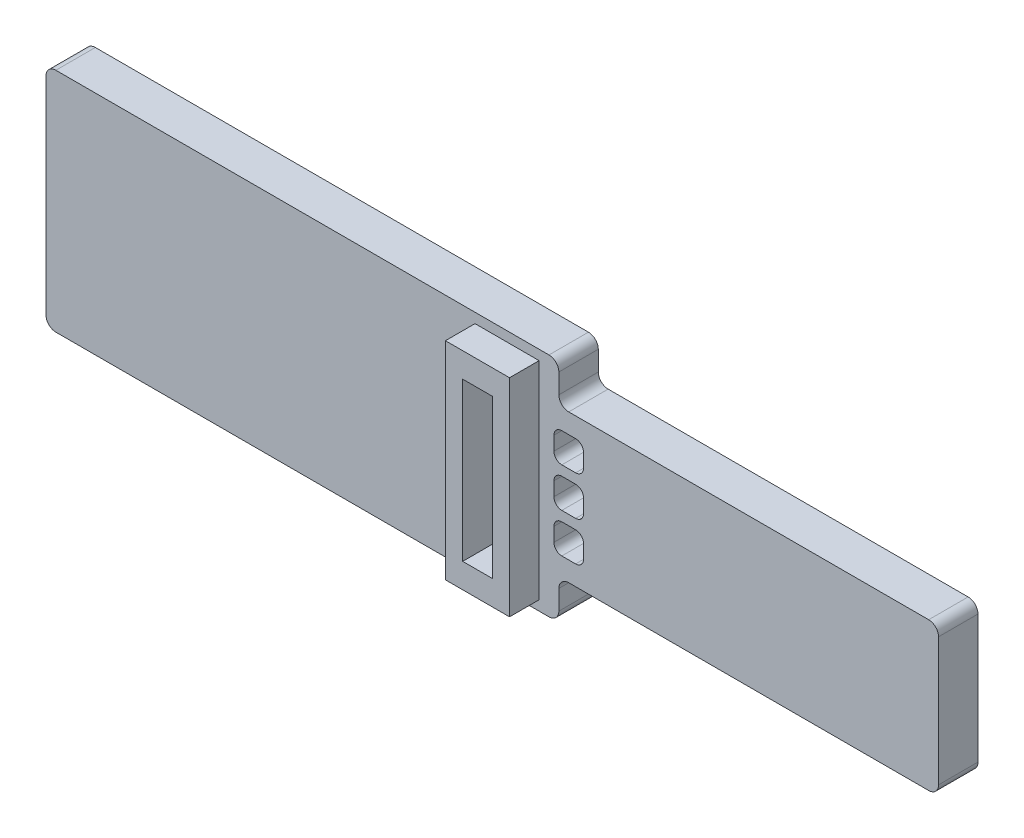
SolidWorks part; units mm, degrees
ref_plane "Front Plane" through (0, 0, 0) normal (0, 0, 1) x (1, 0, 0)
ref_plane "Top Plane" through (0, 0, 0) normal (0, 1, 0) x (1, 0, 0)
ref_plane "Right Plane" through (0, 0, 0) normal (1, 0, 0) x (0, 0, -1)
sketch "Sketch1" plane through (0, 0, 0) normal (0, 0, 1) x (1, 0, 0)
  line L0 (52, 19) -> (63.0723, 19) construction
  line L1 (0, 0) -> (52, 0)
  line L2 (0, 0) -> (0, 23)
  line L3 (0, 23) -> (52, 23)
  line L4 (52, 0) -> (52, 4)
  line L5 (47.5491, 11.5) -> (74.8048, 11.5) construction
  line L6 (52, 4) -> (63.0723, 4) construction
  line L7 (52, 19) -> (52, 23)
  line L8 (52, 19) -> (90.5, 19)
  line L10 (52, 4) -> (90.5, 4)
  line L11 (90.5, 19) -> (90.5, 4)
  dimension "D1" = 4
  dimension "D2" = 90.5
  dimension "D3" = 52
  dimension "D4" = 23
  dimension "D5" = 15
extrude "Boss-Extrude1" add sketch "Sketch1" along normal blind 4
fillet "Fillet1" radius 1 8 edges at (0, 23, 2) (0, 0, 2) (52, 0, 2) (52, 23, 2) (90.5, 19, 2) (90.5, 4, 2) (52, 4, 2) (52, 19, 2)
sketch "Sketch2" plane through (0, 0, 4) normal (0, 0, 1) x (1, 0, 0)
  line L0 (0, 11.5) -> (27.7784, 11.5) construction
  line L1 (43.5, 22) -> (50, 22)
  line L2 (43.5, 22) -> (43.5, 1)
  line L3 (43.5, 1) -> (50, 1)
  line L4 (50, 22) -> (50, 1)
  line L5 (0, 22) -> (0, 1) construction
  line L6 (50, 11.5) -> (43.5, 11.5) construction
  line L9 (48.25, 3.5) -> (45.25, 3.5)
  line L10 (48.25, 3.5) -> (48.25, 19.5)
  line L11 (48.25, 19.5) -> (45.25, 19.5)
  line L12 (45.25, 3.5) -> (45.25, 19.5)
  line L13 (48.25, 3.5) -> (45.25, 19.5) construction
  line L14 (48.25, 19.5) -> (45.25, 3.5) construction
  line L15 (49.5, 1.5) -> (44, 1.5)
  line L16 (49.5, 1.5) -> (49.5, 21.5)
  line L17 (49.5, 21.5) -> (44, 21.5)
  line L18 (44, 1.5) -> (44, 21.5)
  line L19 (49.5, 1.5) -> (44, 21.5) construction
  line L20 (49.5, 21.5) -> (44, 1.5) construction
  point P12 (46.75, 11.5)
  point P17 (46.75, 11.5)
  dimension "D2" = 0.5
  dimension "D3" = 0.5
extrude "Boss-Extrude2" add sketch "Sketch2" along normal blind 3 contours L18 L15 L16 L17 L9 L12 L11 L10 | L2 L3 L4 L1
sketch "Sketch3" plane through (0, 0, 0) normal (0, 0, -1) x (-1, 0, 0)
  line L0 (-53, 24.6979) -> (-53, 6.3021) construction
  line L1 (-90.5, 5) -> (-90.5, 18) construction
  line L5 (-53.7, 14) -> (-52.3, 14)
  line L6 (-54.5, 14.8) -> (-54.5, 16.2)
  line L7 (-53.7, 17) -> (-52.3, 17)
  line L8 (-51.5, 14.8) -> (-51.5, 16.2)
  line L9 (-54.5, 14) -> (-51.5, 17) construction
  line L10 (-54.5, 17) -> (-51.5, 14) construction
  line L11 (-52.3, 10) -> (-53.7, 10)
  line L12 (-51.5, 10.8) -> (-51.5, 12.2)
  line L13 (-52.3, 13) -> (-53.7, 13)
  line L14 (-54.5, 10.8) -> (-54.5, 12.2)
  line L15 (-51.5, 10) -> (-54.5, 13) construction
  line L16 (-51.5, 13) -> (-54.5, 10) construction
  line L17 (-53.7, 6) -> (-52.3, 6)
  line L18 (-54.5, 6.8) -> (-54.5, 8.2)
  line L19 (-53.7, 9) -> (-52.3, 9)
  line L20 (-51.5, 6.8) -> (-51.5, 8.2)
  line L21 (-54.5, 6) -> (-51.5, 9) construction
  line L22 (-54.5, 9) -> (-51.5, 6) construction
  arc A3 (-53.7, 6) -> (-54.5, 6.8) centre (-53.7, 6.8) cw
  arc A4 (-52.3, 6) -> (-51.5, 6.8) centre (-52.3, 6.8) ccw
  arc A5 (-52.3, 10) -> (-51.5, 10.8) centre (-52.3, 10.8) ccw
  arc A6 (-53.7, 10) -> (-54.5, 10.8) centre (-53.7, 10.8) cw
  arc A7 (-53.7, 14) -> (-54.5, 14.8) centre (-53.7, 14.8) cw
  arc A8 (-52.3, 14) -> (-51.5, 14.8) centre (-52.3, 14.8) ccw
  arc A9 (-52.3, 9) -> (-51.5, 8.2) centre (-52.3, 8.2) cw
  arc A10 (-54.5, 8.2) -> (-53.7, 9) centre (-53.7, 8.2) cw
  arc A11 (-53.7, 13) -> (-54.5, 12.2) centre (-53.7, 12.2) ccw
  arc A12 (-51.5, 12.2) -> (-52.3, 13) centre (-52.3, 12.2) ccw
  arc A13 (-52.3, 17) -> (-51.5, 16.2) centre (-52.3, 16.2) cw
  arc A14 (-54.5, 16.2) -> (-53.7, 17) centre (-53.7, 16.2) cw
  dimension "D1" = 37.5
  dimension "D2" = 0.8
extrude "Cut-Extrude3" cut sketch "Sketch3" against normal through all
sketch "Sketch4" plane through (0, 0, 0) normal (0, 0, -1) x (-1, 0, 0)
  line L0 (-90.5, 11.5) -> (-82.5454, 11.5) construction
  line L1 (-71.5, 19) -> (-56.5, 19)
  line L2 (-71.5, 19) -> (-71.5, 4)
  line L3 (-71.5, 4) -> (-56.5, 4)
  line L4 (-56.5, 19) -> (-56.5, 4)
  line L5 (-71.5, 19) -> (-56.5, 4) construction
  line L6 (-71.5, 4) -> (-56.5, 19) construction
  line L7 (-90.5, 5) -> (-90.5, 18) construction
  line L8 (-64, 11.5) -> (-71.5, 11.5) construction
  point P0 (-64, 11.5)
  dimension "D1" = 34
